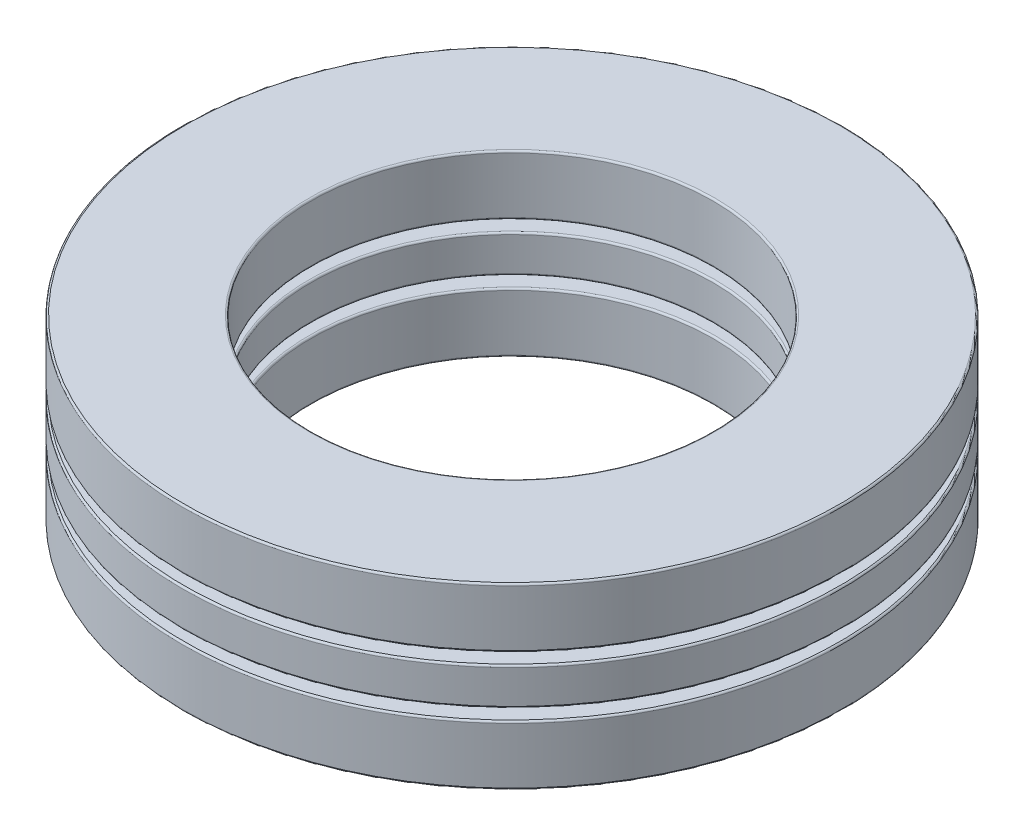
SolidWorks part; units mm, degrees
ref_plane "Front Plane" through (0, 0, 0) normal (0, 0, 1) x (1, 0, 0)
ref_plane "Top Plane" through (0, 0, 0) normal (0, 1, 0) x (1, 0, 0)
ref_plane "Right Plane" through (0, 0, 0) normal (1, 0, 0) x (0, 0, -1)
sketch "Sketch1" plane through (0, 0, 0) normal (1, 0, 0) x (0, 0, -1)
  line L0 (-20.5, 0) -> (20.5, 0) construction
  line L1 (0, -5.555) -> (0, 5.555) construction
  line L2 (-20.5, 1.1573) -> (-12.5, 1.1573)
  line L3 (-20.5, 1.1573) -> (-20.5, -1.1573)
  line L4 (-20.5, -1.1573) -> (-12.5, -1.1573)
  line L5 (-12.5, 1.1573) -> (-12.5, -1.1573)
  line L6 (-16.5, 1.8517) -> (-16.5, -1.8517) construction
  circle A0 centre (-16.5, 0) radius 1.8517 construction
  point P13 (-16.5, 1.1573)
  dimension "D1" = 3.7033
  dimension "OD" = 41
  dimension "Shaft Dia" = 25
  dimension "Th" = 11.11
  dimension "D2" = 2.3146
revolve "Revolve1" add sketch "Sketch1" angle 360 about L1
sketch "Sketch3" plane through (0, 0, 0) normal (1, 0, 0) x (0, 0, -1)
  line L0 (-16.5, 1.8517) -> (-16.5, -1.8517)
  arc A0 (-16.5, 1.8517) -> (-16.5, -1.8517) centre (-16.5, 0) ccw
  circle A1 centre (-16.5, 0) radius 1.8517 construction
revolve "Cut-Revolve1" cut sketch "Sketch3" angle 360 about L0
sketch "Sketch2" plane through (0, 0, 0) normal (1, 0, 0) x (0, 0, -1)
  line L0 (-16.5, 1.8517) -> (-16.5, -1.8517)
  arc A0 (-16.5, 1.8517) -> (-16.5, -1.8517) centre (-16.5, 0) ccw
  circle A2 centre (-16.5, 0) radius 1.8517 construction
revolve "Revolve2" add sketch "Sketch2" angle 360 about L0
ref_axis "Axis1" through (0, 5.555, 0) along (0, -1, 0)
pattern_circular "CirPattern1" count 10 every 36 about axis through (0, 5.555, 0) along (0, -1, 0) of bodies 187
pattern_circular "CirPattern2" count 10 every 36 about axis through (0, 0, 0) along (0, 1, 0) of "Cut-Revolve1"
sketch "Sketch4" plane through (0, 0, 0) normal (1, 0, 0) x (0, 0, -1)
  line L0 (-20.5, 1.1573) -> (-20.5, -1.1573) construction
  line L1 (-20.5, 1.8517) -> (-12.5, 1.8517)
  line L2 (-20.5, 1.8517) -> (-20.5, 5.555)
  line L3 (-20.5, 5.555) -> (-12.5, 5.555)
  line L4 (-12.5, 1.8517) -> (-12.5, 5.555)
  line L5 (-20.5, -5.555) -> (-12.5, -5.555)
  line L6 (-20.5, -5.555) -> (-20.5, -1.8517)
  line L7 (-20.5, -1.8517) -> (-12.5, -1.8517)
  line L8 (-12.5, -5.555) -> (-12.5, -1.8517)
  line L9 (-16.5, 1.8517) -> (-16.5, -1.8517) construction
  line L10 (-12.5, 1.1573) -> (-12.5, -1.1573) construction
  line L11 (0, 0) -> (-20.5, 0) construction
  line L12 (-20.5, 0) -> (20.5, 0) construction
  dimension "Ht" = 11.11
revolve "Revolve3" add sketch "Sketch4" angle 360 about L1
fillet "Fillet1" radius 0.1111 4 edges at (0, 1.8517, -12.5) (0, 5.555, -12.5) (0, 1.8517, -20.5) (0, 5.555, -20.5)
fillet "Fillet2" radius 0.1111 4 edges at (0, -1.1573, -12.5) (0, 1.1573, -12.5) (0, -1.1573, -20.5) (0, 1.1573, -20.5)
fillet "Fillet3" radius 0.1111 4 edges at (0, -5.555, -12.5) (0, -1.8517, -12.5) (0, -5.555, -20.5) (0, -1.8517, -20.5)
equation "\"D1@Sketch1\" = \"Th@Sketch1\"/3"
equation "\"D2@Sketch1\" = \"D1@Sketch1\"*.625"
equation "\"Balls@CirPattern1\" = \"OD@Sketch1\"*.25"
equation "\"Angle@CirPattern1\" = 360/\"Balls@CirPattern1\""
equation "\"D1@CirPattern2\" = \"Balls@CirPattern1\""
equation "\"D2@CirPattern2\" = \"Angle@CirPattern1\""
equation "\"D1@Fillet1\" = \"Th@Sketch1\"*.01"
equation "\"D1@Fillet2\" = \"D1@Fillet1\""
equation "\"D1@Fillet3\" = \"D1@Fillet1\""
